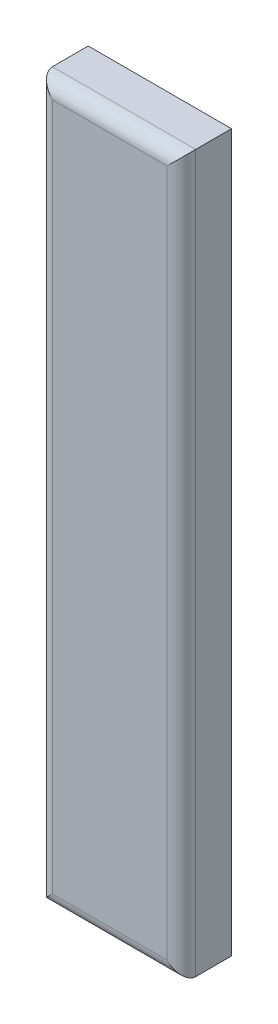
SolidWorks part; units mm, degrees
ref_plane "Front Plane" through (0, 0, 0) normal (0, 0, 1) x (1, 0, 0)
ref_plane "Top Plane" through (0, 0, 0) normal (0, 1, 0) x (1, 0, 0)
ref_plane "Right Plane" through (0, 0, 0) normal (1, 0, 0) x (0, 0, -1)
sketch "Sketch1" plane through (0, 0, 0) normal (0, 0, 1) x (1, 0, 0)
  line L1 (-10, 50) -> (10, 50)
  line L2 (-10, 50) -> (-10, -50)
  line L3 (-10, -50) -> (10, -50)
  line L4 (10, 50) -> (10, -50)
  line L5 (-10, 50) -> (10, -50) construction
  line L6 (-10, -50) -> (10, 50) construction
  point P0 (0, 0)
  dimension "D1" = 20
  dimension "D2" = 100
extrude "Boss-Extrude1" add sketch "Sketch1" along normal blind 7
fillet "Fillet1" radius 2 4 edges at (-10, 0, 7) (0, -50, 7) (10, 0, 7) (0, 50, 7)
